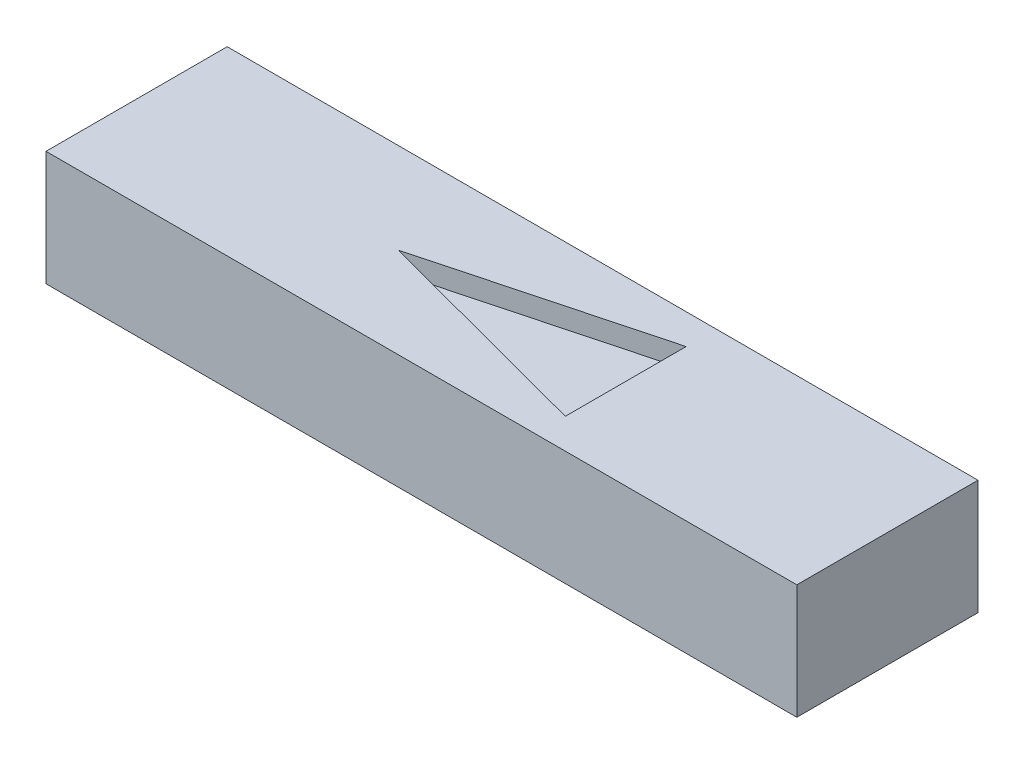
SolidWorks part; units mm, degrees
ref_plane "Front Plane" through (0, 0, 0) normal (0, 0, 1) x (1, 0, 0)
ref_plane "Top Plane" through (0, 0, 0) normal (0, 1, 0) x (1, 0, 0)
ref_plane "Right Plane" through (0, 0, 0) normal (1, 0, 0) x (0, 0, -1)
sketch "Sketch2" plane through (0, 0, 0) normal (0, 1, 0) x (1, 0, 0)
  line L1 (0, 0) -> (37.3, 0)
  line L2 (0, 0) -> (0, 9)
  line L3 (0, 9) -> (37.3, 9)
  line L4 (37.3, 0) -> (37.3, 9)
  dimension "D1" = 37.3
  dimension "D2" = 9
extrude "Boss-Extrude1" add sketch "Sketch2" along normal blind 5.7
sketch "Sketch3" plane through (0, 5.7, 0) normal (0, 1, 0) x (1, 0, 0)
  line L0 (0, 0) -> (37.3, 0) construction
  line L1 (24.3, 1.5) -> (13, 1.5)
  line L2 (24.3, 1.5) -> (24.3, 7.5)
  line L3 (24.3, 7.5) -> (13, 7.5)
  line L4 (13, 1.5) -> (13, 7.5)
  line L5 (37.3, 9) -> (0, 9) construction
  line L6 (0, 9) -> (0, 0) construction
  line L7 (37.3, 0) -> (37.3, 9) construction
  line L8 (24.3, 7.5) -> (13, 4.5)
  line L9 (13, 4.5) -> (24.3, 1.5)
  dimension "D1" = 1.5
  dimension "D3" = 1.5
  dimension "D4" = 13
  dimension "D5" = 13
extrude "Cut-Extrude1" cut sketch "Sketch3" against normal blind 1 contours L8 L9 L2
